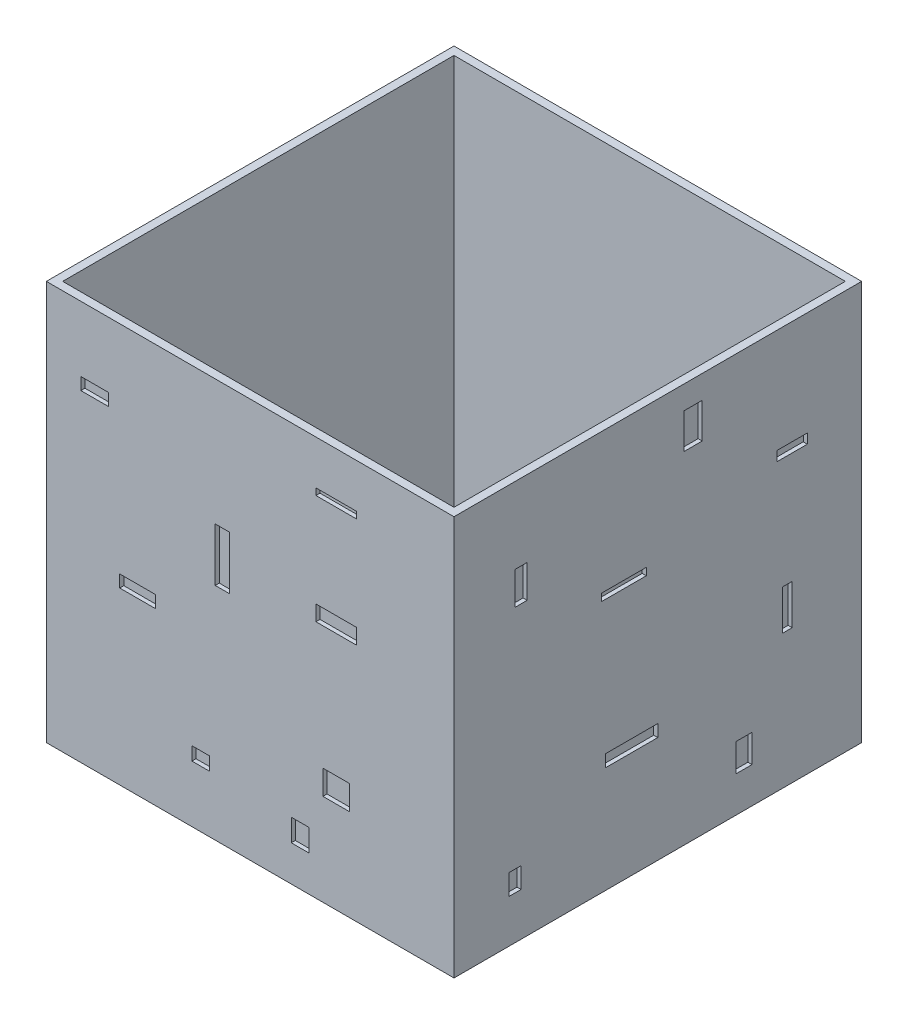
SolidWorks part; units mm, degrees
ref_plane "Ön Düzlem" through (0, 0, 0) normal (0, 0, 1) x (1, 0, 0)
ref_plane "Üst Düzlem" through (0, 0, 0) normal (0, 1, 0) x (1, 0, 0)
ref_plane "Sağ Düzlem" through (0, 0, 0) normal (1, 0, 0) x (0, 0, -1)
sketch "Çizim1" plane through (0, 0, 0) normal (0, 1, 0) x (1, 0, 0)
  line L1 (-50, 50) -> (50, 50)
  line L2 (-50, 50) -> (-50, -50)
  line L3 (-50, -50) -> (50, -50)
  line L4 (50, 50) -> (50, -50)
  line L5 (-50, 50) -> (50, -50) construction
  line L6 (-50, -50) -> (50, 50) construction
  circle A0 centre (0, 0) radius 24.5
  point P0 (0, 0)
  dimension "D3" = 49
  dimension "D1" = 100
  dimension "D2" = 100
extrude "Yükseklik-Ekstrüzyon1" add sketch "Çizim1" along normal blind 2
sketch "Çizim2" plane through (0, 2, 0) normal (0, 1, 0) x (1, 0, 0)
  line L1 (-50, 50) -> (50, 50)
  line L2 (-50, 50) -> (-50, -50)
  line L3 (-50, -50) -> (50, -50)
  line L4 (50, 50) -> (50, -50)
  line L5 (-50, 50) -> (50, -50) construction
  line L6 (-50, -50) -> (50, 50) construction
  line L7 (-48, 48) -> (48, 48)
  line L8 (-48, 48) -> (-48, -48)
  line L9 (-48, -48) -> (48, -48)
  line L10 (48, 48) -> (48, -48)
  line L11 (-48, 48) -> (48, -48) construction
  line L12 (-48, -48) -> (48, 48) construction
  point P0 (0, 0)
  point P7 (0, 0)
  dimension "D1" = 96
  dimension "D2" = 96
extrude "Yükseklik-Ekstrüzyon2" add sketch "Çizim2" along normal blind 96
sketch "Çizim3" plane through (0, 0, 50) normal (0, 0, 1) x (1, 0, 0)
  line L1 (-41.5331, 82.0222) -> (-34.7244, 82.0222)
  line L2 (-41.5331, 82.0222) -> (-41.5331, 79.0264)
  line L3 (-41.5331, 79.0264) -> (-34.7244, 79.0264)
  line L4 (-34.7244, 82.0222) -> (-34.7244, 79.0264)
  line L5 (-41.5331, 82.0222) -> (-34.7244, 79.0264) construction
  line L6 (-41.5331, 79.0264) -> (-34.7244, 82.0222) construction
  line L7 (-8.579, 67.1792) -> (-5.0384, 67.1792)
  line L8 (-8.579, 67.1792) -> (-8.579, 54.1065)
  line L9 (-8.579, 54.1065) -> (-5.0384, 54.1065)
  line L10 (-5.0384, 67.1792) -> (-5.0384, 54.1065)
  line L11 (-8.579, 67.1792) -> (-5.0384, 54.1065) construction
  line L12 (-8.579, 54.1065) -> (-5.0384, 67.1792) construction
  line L13 (-32.0009, 44.8467) -> (-23.2857, 44.8467)
  line L14 (-32.0009, 44.8467) -> (-32.0009, 41.8509)
  line L15 (-32.0009, 41.8509) -> (-23.2857, 41.8509)
  line L16 (-23.2857, 44.8467) -> (-23.2857, 41.8509)
  line L17 (-32.0009, 44.8467) -> (-23.2857, 41.8509) construction
  line L18 (-32.0009, 41.8509) -> (-23.2857, 44.8467) construction
  line L19 (16.1274, 62.5362) -> (26.0865, 62.5362)
  line L20 (16.1274, 62.5362) -> (16.1274, 58.7495)
  line L21 (16.1274, 58.7495) -> (26.0865, 58.7495)
  line L22 (26.0865, 62.5362) -> (26.0865, 58.7495)
  line L23 (16.1274, 62.5362) -> (26.0865, 58.7495) construction
  line L24 (16.1274, 58.7495) -> (26.0865, 62.5362) construction
  line L25 (17.8388, 28.5058) -> (24.3751, 28.5058)
  line L26 (17.8388, 28.5058) -> (17.8388, 22.5142)
  line L27 (17.8388, 22.5142) -> (24.3751, 22.5142)
  line L28 (24.3751, 28.5058) -> (24.3751, 22.5142)
  line L29 (17.8388, 28.5058) -> (24.3751, 22.5142) construction
  line L30 (17.8388, 22.5142) -> (24.3751, 28.5058) construction
  line L31 (-14.2983, 17.2034) -> (-9.9407, 17.2034)
  line L32 (-14.2983, 17.2034) -> (-14.2983, 13.9352)
  line L33 (-14.2983, 13.9352) -> (-9.9407, 13.9352)
  line L34 (-9.9407, 17.2034) -> (-9.9407, 13.9352)
  line L35 (-14.2983, 17.2034) -> (-9.9407, 13.9352) construction
  line L36 (-14.2983, 13.9352) -> (-9.9407, 17.2034) construction
  line L37 (10.0769, 14.2076) -> (14.4344, 14.2076)
  line L38 (10.0769, 14.2076) -> (10.0769, 8.7606)
  line L39 (10.0769, 8.7606) -> (14.4344, 8.7606)
  line L40 (14.4344, 14.2076) -> (14.4344, 8.7606)
  line L41 (10.0769, 14.2076) -> (14.4344, 8.7606) construction
  line L42 (10.0769, 8.7606) -> (14.4344, 14.2076) construction
  line L43 (16.1274, 87.1968) -> (26.0865, 87.1968)
  line L44 (16.1274, 87.1968) -> (16.1274, 85.5627)
  line L45 (16.1274, 85.5627) -> (26.0865, 85.5627)
  line L46 (26.0865, 87.1968) -> (26.0865, 85.5627)
  line L47 (16.1274, 87.1968) -> (26.0865, 85.5627) construction
  line L48 (16.1274, 85.5627) -> (26.0865, 87.1968) construction
  point P0 (-38.1287, 80.5243)
  point P5 (-6.8087, 60.6429)
  point P10 (-27.6433, 43.3488)
  point P15 (21.107, 60.6429)
  point P20 (21.107, 25.51)
  point P25 (-12.1195, 15.5693)
  point P30 (12.2557, 11.4841)
  point P35 (21.107, 86.3797)
extrude "Kes-Ekstrüzyon1" cut sketch "Çizim3" against normal blind 1
sketch "Çizim4" plane through (-50, 0, 0) normal (-1, 0, 0) x (0, 0, 1)
  line L1 (-41.5508, 86.5968) -> (-38.6956, 86.5968)
  line L2 (-41.5508, 86.5968) -> (-41.5508, 81.7356)
  line L3 (-41.5508, 81.7356) -> (-38.6956, 81.7356)
  line L4 (-38.6956, 86.5968) -> (-38.6956, 81.7356)
  line L5 (-41.5508, 86.5968) -> (-38.6956, 81.7356) construction
  line L6 (-41.5508, 81.7356) -> (-38.6956, 86.5968) construction
  line L7 (-5.6595, 48.9264) -> (5.6595, 48.9264)
  line L8 (-5.6595, 48.9264) -> (-5.6595, 47.1959)
  line L9 (-5.6595, 47.1959) -> (5.6595, 47.1959)
  line L10 (5.6595, 48.9264) -> (5.6595, 47.1959)
  line L11 (-5.6595, 48.9264) -> (5.6595, 47.1959) construction
  line L12 (-5.6595, 47.1959) -> (5.6595, 48.9264) construction
  line L13 (11.0297, 73.9067) -> (13.7442, 73.9067)
  line L14 (11.0297, 73.9067) -> (11.0297, 63.5839)
  line L15 (11.0297, 63.5839) -> (13.7442, 63.5839)
  line L16 (13.7442, 73.9067) -> (13.7442, 63.5839)
  line L17 (11.0297, 73.9067) -> (13.7442, 63.5839) construction
  line L18 (11.0297, 63.5839) -> (13.7442, 73.9067) construction
  line L19 (21.5863, 56.2205) -> (30.9735, 56.2205)
  line L20 (21.5863, 56.2205) -> (21.5863, 52.843)
  line L21 (21.5863, 52.843) -> (30.9735, 52.843)
  line L22 (30.9735, 56.2205) -> (30.9735, 52.843)
  line L23 (21.5863, 56.2205) -> (30.9735, 52.843) construction
  line L24 (21.5863, 52.843) -> (30.9735, 56.2205) construction
  line L25 (-29.2957, 38.5071) -> (-24.3065, 38.5071)
  line L26 (-29.2957, 38.5071) -> (-29.2957, 24.6773)
  line L27 (-29.2957, 24.6773) -> (-24.3065, 24.6773)
  line L28 (-24.3065, 38.5071) -> (-24.3065, 24.6773)
  line L29 (-29.2957, 38.5071) -> (-24.3065, 24.6773) construction
  line L30 (-29.2957, 24.6773) -> (-24.3065, 38.5071) construction
  line L31 (3.741, 19.7016) -> (11.0297, 19.7016)
  line L32 (3.741, 19.7016) -> (3.741, 13.8)
  line L33 (3.741, 13.8) -> (11.0297, 13.8)
  line L34 (11.0297, 19.7016) -> (11.0297, 13.8)
  line L35 (3.741, 19.7016) -> (11.0297, 13.8) construction
  line L36 (3.741, 13.8) -> (11.0297, 19.7016) construction
  line L37 (28.2949, 21.2217) -> (33.652, 21.2217)
  line L38 (28.2949, 21.2217) -> (28.2949, 15.9066)
  line L39 (28.2949, 15.9066) -> (33.652, 15.9066)
  line L40 (33.652, 21.2217) -> (33.652, 15.9066)
  line L41 (28.2949, 21.2217) -> (33.652, 15.9066) construction
  line L42 (28.2949, 15.9066) -> (33.652, 21.2217) construction
  line L43 (-16.4495, 77.4277) -> (-18.7899, 77.4277)
  line L44 (-16.4495, 77.4277) -> (-16.4495, 68.3674)
  line L45 (-16.4495, 68.3674) -> (-18.7899, 68.3674)
  line L46 (-18.7899, 77.4277) -> (-18.7899, 68.3674)
  line L47 (-16.4495, 77.4277) -> (-18.7899, 68.3674) construction
  line L48 (-16.4495, 68.3674) -> (-18.7899, 77.4277) construction
  point P0 (-40.1232, 84.1662)
  point P5 (0, 48.0611)
  point P10 (12.3869, 68.7453)
  point P15 (26.2799, 54.5318)
  point P20 (-26.8011, 31.5922)
  point P25 (7.3853, 16.7508)
  point P30 (30.9735, 18.5642)
  point P35 (-17.6197, 72.8975)
extrude "Kes-Ekstrüzyon2" cut sketch "Çizim4" against normal blind 1
sketch "Çizim5" plane through (0, 0, -50) normal (0, 0, -1) x (-1, 0, 0)
  line L1 (-31.32, 75.622) -> (-28.3242, 75.622)
  line L2 (-31.32, 75.622) -> (-31.32, 71.2644)
  line L3 (-31.32, 71.2644) -> (-28.3242, 71.2644)
  line L4 (-28.3242, 75.622) -> (-28.3242, 71.2644)
  line L5 (-31.32, 75.622) -> (-28.3242, 71.2644) construction
  line L6 (-31.32, 71.2644) -> (-28.3242, 75.622) construction
  line L7 (-12.528, 67.9963) -> (-1.3617, 67.9963)
  line L8 (-12.528, 67.9963) -> (-12.528, 66.3622)
  line L9 (-12.528, 66.3622) -> (-1.3617, 66.3622)
  line L10 (-1.3617, 67.9963) -> (-1.3617, 66.3622)
  line L11 (-12.528, 67.9963) -> (-1.3617, 66.3622) construction
  line L12 (-12.528, 66.3622) -> (-1.3617, 67.9963) construction
  line L13 (23.5581, 49.6128) -> (26.5539, 49.6128)
  line L14 (23.5581, 49.6128) -> (23.5581, 41.987)
  line L15 (23.5581, 41.987) -> (26.5539, 41.987)
  line L16 (26.5539, 49.6128) -> (26.5539, 41.987)
  line L17 (23.5581, 49.6128) -> (26.5539, 41.987) construction
  line L18 (23.5581, 41.987) -> (26.5539, 49.6128) construction
  line L19 (9.8045, 33.9528) -> (2.4511, 33.9528)
  line L20 (9.8045, 33.9528) -> (9.8045, 29.5952)
  line L21 (9.8045, 29.5952) -> (2.4511, 29.5952)
  line L22 (2.4511, 33.9528) -> (2.4511, 29.5952)
  line L23 (9.8045, 33.9528) -> (2.4511, 29.5952) construction
  line L24 (9.8045, 29.5952) -> (2.4511, 33.9528) construction
  line L25 (-30.2306, 26.1909) -> (-26.4177, 26.1909)
  line L26 (-30.2306, 26.1909) -> (-30.2306, 17.7481)
  line L27 (-30.2306, 17.7481) -> (-26.4177, 17.7481)
  line L28 (-26.4177, 26.1909) -> (-26.4177, 17.7481)
  line L29 (-30.2306, 26.1909) -> (-26.4177, 17.7481) construction
  line L30 (-30.2306, 17.7481) -> (-26.4177, 26.1909) construction
  line L31 (20.5623, 17.4757) -> (29.5497, 17.4757)
  line L32 (20.5623, 17.4757) -> (20.5623, 15.0246)
  line L33 (20.5623, 15.0246) -> (29.5497, 15.0246)
  line L34 (29.5497, 17.4757) -> (29.5497, 15.0246)
  line L35 (20.5623, 17.4757) -> (29.5497, 15.0246) construction
  line L36 (20.5623, 15.0246) -> (29.5497, 17.4757) construction
  line L37 (17.2941, 81.886) -> (20.5623, 81.886)
  line L38 (17.2941, 81.886) -> (17.2941, 75.622)
  line L39 (17.2941, 75.622) -> (20.5623, 75.622)
  line L40 (20.5623, 81.886) -> (20.5623, 75.622)
  line L41 (17.2941, 81.886) -> (20.5623, 75.622) construction
  line L42 (17.2941, 75.622) -> (20.5623, 81.886) construction
  point P0 (-29.8221, 73.4432)
  point P5 (-6.9449, 67.1792)
  point P10 (25.056, 45.7999)
  point P15 (6.1278, 31.774)
  point P20 (-28.3242, 21.9695)
  point P25 (25.056, 16.2502)
  point P30 (18.9282, 78.754)
extrude "Kes-Ekstrüzyon3" cut sketch "Çizim5" against normal blind 1
sketch "Çizim6" plane through (50, 0, 0) normal (1, 0, 0) x (0, 0, -1)
  line L1 (-35.0388, 79.3126) -> (-32.0568, 79.3126)
  line L2 (-35.0388, 79.3126) -> (-35.0388, 71.2611)
  line L3 (-35.0388, 71.2611) -> (-32.0568, 71.2611)
  line L4 (-32.0568, 79.3126) -> (-32.0568, 71.2611)
  line L5 (-35.0388, 79.3126) -> (-32.0568, 71.2611) construction
  line L6 (-35.0388, 71.2611) -> (-32.0568, 79.3126) construction
  line L7 (-13.8664, 63.6569) -> (-2.8329, 63.6569)
  line L8 (-13.8664, 63.6569) -> (-13.8664, 61.8677)
  line L9 (-13.8664, 61.8677) -> (-2.8329, 61.8677)
  line L10 (-2.8329, 63.6569) -> (-2.8329, 61.8677)
  line L11 (-13.8664, 63.6569) -> (-2.8329, 61.8677) construction
  line L12 (-13.8664, 61.8677) -> (-2.8329, 63.6569) construction
  line L13 (30.5658, 42.7827) -> (32.9514, 42.7827)
  line L14 (30.5658, 42.7827) -> (30.5658, 32.942)
  line L15 (30.5658, 32.942) -> (32.9514, 32.942)
  line L16 (32.9514, 42.7827) -> (32.9514, 32.942)
  line L17 (30.5658, 42.7827) -> (32.9514, 32.942) construction
  line L18 (30.5658, 32.942) -> (32.9514, 42.7827) construction
  line L19 (36.6789, 70.0683) -> (29.2239, 70.0683)
  line L20 (36.6789, 70.0683) -> (36.6789, 72.4539)
  line L21 (36.6789, 72.4539) -> (29.2239, 72.4539)
  line L22 (29.2239, 70.0683) -> (29.2239, 72.4539)
  line L23 (36.6789, 70.0683) -> (29.2239, 72.4539) construction
  line L24 (36.6789, 72.4539) -> (29.2239, 70.0683) construction
  line L25 (-12.8227, 29.0654) -> (0, 29.0654)
  line L26 (-12.8227, 29.0654) -> (-12.8227, 26.0834)
  line L27 (-12.8227, 26.0834) -> (0, 26.0834)
  line L28 (0, 29.0654) -> (0, 26.0834)
  line L29 (-12.8227, 29.0654) -> (0, 26.0834) construction
  line L30 (-12.8227, 26.0834) -> (0, 29.0654) construction
  line L31 (-36.5298, 15.6463) -> (-33.5478, 15.6463)
  line L32 (-36.5298, 15.6463) -> (-36.5298, 10.5769)
  line L33 (-36.5298, 10.5769) -> (-33.5478, 10.5769)
  line L34 (-33.5478, 15.6463) -> (-33.5478, 10.5769)
  line L35 (-36.5298, 15.6463) -> (-33.5478, 10.5769) construction
  line L36 (-36.5298, 10.5769) -> (-33.5478, 15.6463) construction
  line L37 (19.2341, 8.7876) -> (23.1107, 8.7876)
  line L38 (19.2341, 8.7876) -> (19.2341, 15.6463)
  line L39 (19.2341, 15.6463) -> (23.1107, 15.6463)
  line L40 (23.1107, 8.7876) -> (23.1107, 15.6463)
  line L41 (19.2341, 8.7876) -> (23.1107, 15.6463) construction
  line L42 (19.2341, 15.6463) -> (23.1107, 8.7876) construction
  line L43 (6.4114, 92.2844) -> (10.8844, 92.2844)
  line L44 (6.4114, 92.2844) -> (6.4114, 83.6365)
  line L45 (6.4114, 83.6365) -> (10.8844, 83.6365)
  line L46 (10.8844, 92.2844) -> (10.8844, 83.6365)
  line L47 (6.4114, 92.2844) -> (10.8844, 83.6365) construction
  line L48 (6.4114, 83.6365) -> (10.8844, 92.2844) construction
  point P0 (-33.5478, 75.2868)
  point P5 (-8.3497, 62.7623)
  point P10 (31.7586, 37.8624)
  point P15 (32.9514, 71.2611)
  point P20 (-6.4114, 27.5744)
  point P25 (-35.0388, 13.1116)
  point P30 (21.1724, 12.217)
  point P35 (8.6479, 87.9604)
extrude "Kes-Ekstrüzyon4" cut sketch "Çizim6" against normal blind 1
